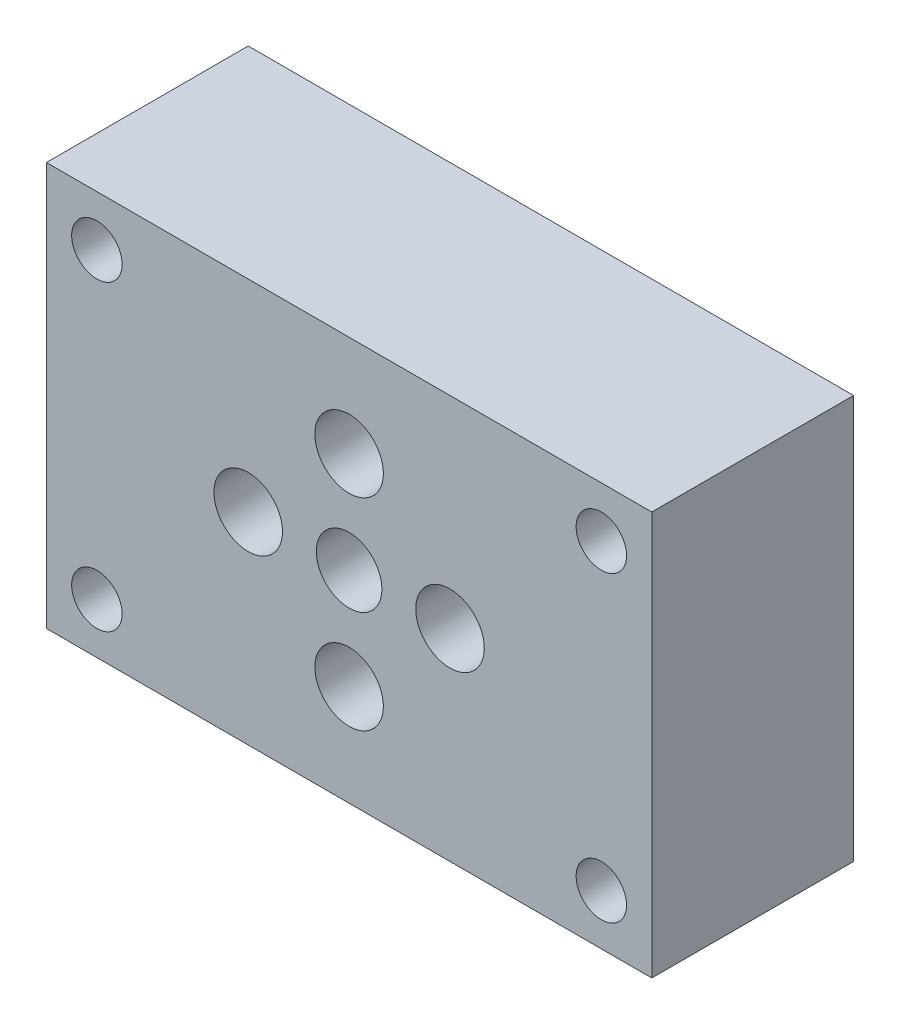
SolidWorks part; units mm, degrees
ref_plane "Front Plane" through (0, 0, 0) normal (0, 0, 1) x (1, 0, 0)
ref_plane "Top Plane" through (0, 0, 0) normal (0, 1, 0) x (1, 0, 0)
ref_plane "Right Plane" through (0, 0, 0) normal (1, 0, 0) x (0, 0, -1)
sketch "Sketch1" plane through (0, 0, 0) normal (0, 0, 1) x (1, 0, 0)
  line L0 (38.1, 25.4) -> (38.1, 38.1) construction
  line L1 (0, 0) -> (76.2, 0)
  line L2 (0, 0) -> (0, 50.8)
  line L3 (0, 50.8) -> (76.2, 50.8)
  line L4 (76.2, 0) -> (76.2, 50.8)
  circle A0 centre (38.1, 38.1) radius 4.3137
  circle A1 centre (50.8, 25.4) radius 4.3137
  circle A2 centre (38.1, 12.7) radius 4.3137
  circle A3 centre (25.4, 25.4) radius 4.3137
  point P7 (38.1, 26.031)
  dimension "D1" = 76.2
  dimension "D2" = 50.8
  dimension "D4" = 12.7
  dimension "D3" = 4
sketch "Sketch4" plane through (0, 0, 0) normal (0, 0, 1) x (1, 0, 0)
  circle A0 centre (38.1, 38.1) radius 4.3137
extrude "Boss-Extrude2" add sketch "Sketch1" along normal blind 25.4
sketch "Sketch6" plane through (0, 0, 25.4) normal (0, 0, 1) x (1, 0, 0)
  circle A0 centre (38.1, 25.4) radius 4.1275
  circle A1 centre (6.35, 44.45) radius 3.175
  circle A2 centre (69.85, 44.45) radius 3.175
  circle A3 centre (6.35, 6.35) radius 3.175
  circle A4 centre (69.85, 6.35) radius 3.175
  dimension "D1" = 2
  dimension "D2" = 2
  dimension "D3" = 2
extrude "Cut-Extrude3" cut sketch "Sketch6" against normal blind 25.4
